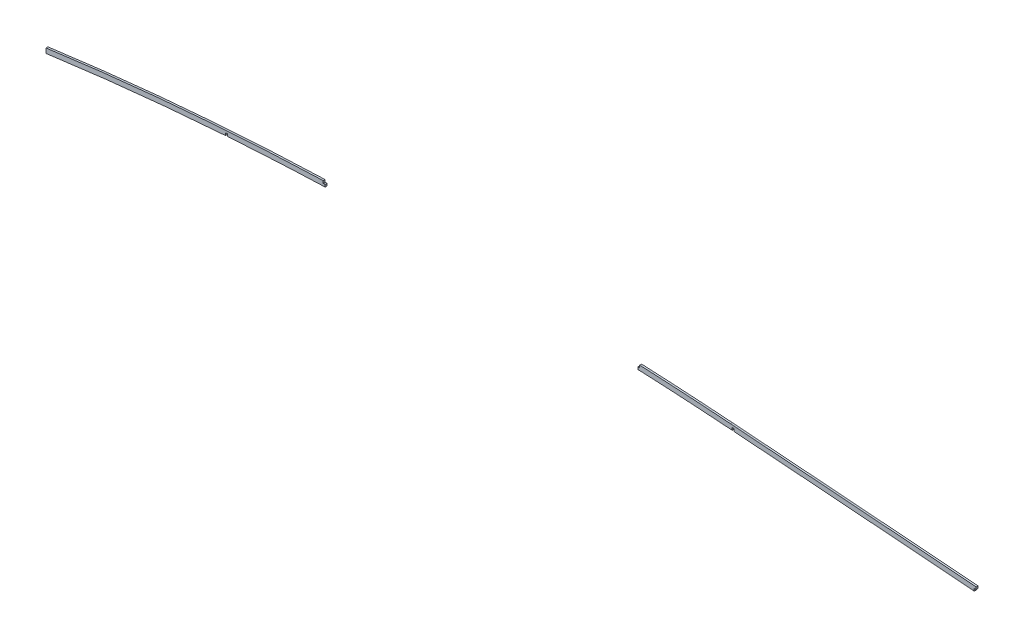
SolidWorks part; units mm, degrees
ref_plane "Front Plane" through (0, 0, 0) normal (0, 0, 1) x (1, 0, 0)
ref_plane "Top Plane" through (0, 0, 0) normal (0, 1, 0) x (1, 0, 0)
ref_plane "Right Plane" through (0, 0, 0) normal (1, 0, 0) x (0, 0, -1)
sketch "Sketch1" plane through (0, 0, 0) normal (0, 0, 1) x (1, 0, 0)
  line L0 (-873.1569, -405.6275) -> (-893.4769, -405.6275) construction
  line L1 (-475.0067, 408.1208) -> (-57.6776, 408.1208)
  line L2 (-475.0067, 382.7208) -> (-57.6776, 382.7208)
  line L3 (-2497.0067, 266.7561) -> (-2493.4723, 241.6032)
  line L4 (2501.9933, 263.2258) -> (2500.0175, 237.9028)
  line L5 (-475.0067, 382.7208) -> (-475.0067, 313.855)
  line L7 (-2493.4723, 241.6032) -> (-2493.4723, 201.2091)
  line L8 (701.2517, 340.7501) -> (691.2517, 340.7501)
  line L10 (691.2517, 340.7501) -> (691.2517, 353.2501)
  line L11 (691.2517, 353.2501) -> (701.2517, 353.2501)
  line L12 (701.2517, 353.2501) -> (701.2517, 365.7751)
  line L13 (2500.0175, 237.9028) -> (2500.0175, 197.7812)
  line L14 (1179.4301, 312.5902) -> (1179.4301, 325.0902) construction
  line L15 (1179.4301, 325.0902) -> (1189.4301, 325.0902) construction
  line L16 (1189.4301, 325.0902) -> (1189.4301, 311.8594) construction
  line L17 (1181.2517, 293.855) -> (1181.2517, 188.8411) construction
  line L18 (-2443.4723, 223.3063) -> (-2443.4723, 248.5402)
  line L19 (2483.0775, 239.2239) -> (2483.0775, 214.1481)
  line L20 (935.6747, 353.6794) -> (935.6747, 9.4968) construction
  line L21 (681.2517, 366.6569) -> (681.2517, 111.1326)
  line L22 (-975.0067, 374.1011) -> (-975.0067, 83.1429)
  line L23 (-975.0067, 349.0863) -> (-965.0067, 349.0863)
  line L24 (-965.0067, 349.0863) -> (-965.0067, 361.5863)
  line L25 (-965.0067, 361.5863) -> (-975.0067, 361.5863)
  line L26 (701.2517, 325.7351) -> (701.2517, 340.7501)
  line L27 (1201.2501, 336.0619) -> (1201.2501, 310.9951)
  line L28 (1191.2501, 324.2264) -> (1201.2501, 324.2264)
  line L29 (1191.2501, 324.2264) -> (1191.2501, 311.7264)
  line L30 (2483.0775, 226.686) -> (2473.0775, 226.686)
  line L31 (2473.0775, 226.686) -> (2473.0775, 214.9276)
  line L32 (-1482.3467, 40.0604) -> (-1482.3467, 248.5402)
  line L33 (-1482.3467, 248.5402) -> (-1482.3467, 322.6417)
  line L34 (-1482.3467, 322.6417) -> (-1482.3467, 335.1417)
  line L35 (-1482.3467, 335.1417) -> (-1492.3467, 335.1417)
  line L36 (-1492.3467, 335.1417) -> (-1492.3467, 321.9409)
  line L38 (-475.0067, 357.7208) -> (-57.6776, 357.7208) construction
  arc A0 (1183.1025, 362.8562) -> (806.4225, 386.1827) centre (-57.6776, -16620.4625) ccw
  arc A1 (806.4225, 386.1827) -> (539.7225, 397.6385) centre (-57.6776, -16620.4625) ccw
  arc A2 (539.7225, 397.6385) -> (-57.6776, 408.1208) centre (-57.6776, -16620.4625) ccw
  arc A3 (-475.0067, 408.1208) -> (-2497.0067, 266.7561) centre (-475.0067, -14123.328) ccw construction
  arc A4 (1183.1025, 362.8562) -> (2501.9933, 263.2258) centre (-18336.3105, -266811.34) cw construction
  arc A5 (1181.2517, 337.5237) -> (2500.0175, 237.9028) centre (-18336.3105, -266811.34) cw
  arc A6 (1181.2517, 337.5237) -> (805.1336, 360.8154) centre (-57.6776, -16620.4625) ccw
  arc A7 (805.1336, 360.8154) -> (538.8314, 372.2542) centre (-57.6776, -16620.4625) ccw
  arc A8 (538.8314, 372.2542) -> (-57.6776, 382.7208) centre (-57.6776, -16620.4625) ccw
  arc A9 (-475.0067, 382.7208) -> (-2493.4723, 241.6032) centre (-475.0067, -14123.328) ccw
  arc A10 (-975.0067, 349.0863) -> (-2443.4723, 223.3063) centre (-475.0067, -14123.328) ccw
  arc A11 (803.865, 335.8476) -> (537.9544, 347.2695) centre (-57.6776, -16620.4625) ccw construction
  arc A12 (803.865, 335.8476) -> (701.2517, 340.7501) centre (-57.6776, -16620.4625) ccw
  arc A13 (1179.4301, 312.5902) -> (803.865, 335.8476) centre (-57.6776, -16620.4625) ccw
  arc A14 (1179.4301, 312.5902) -> (2498.0728, 212.9785) centre (-18336.3105, -266811.34) cw construction
  arc A16 (1179.4301, 312.5902) -> (2483.0775, 214.1481) centre (-18336.3105, -266811.34) cw
  arc A17 (-475.0067, 357.7208) -> (-2489.9937, 216.8464) centre (-475.0067, -14123.328) ccw construction
  arc A20 (537.9544, 347.2695) -> (-57.6776, 357.7208) centre (-57.6776, -16620.4625) ccw construction
  dimension "D1" = 14531.4488
  dimension "D2" = 267886.2793
  dimension "D3" = 17028.5833
  dimension "D4" = 17028.5833
  dimension "D21" = 10
  dimension "D10" = 12.5
  dimension "D27" = 25
  dimension "D5" = 417.3291
  dimension "D6" = 4999
  dimension "D7" = 2022
  dimension "D8" = 1318.8908
  dimension "D9" = 1658.1092
  dimension "D11" = 10
  dimension "D12" = 12.5
  dimension "D14" = 11.82
  dimension "D15" = 25
  dimension "D16" = 50
  dimension "D17" = 16.94
  dimension "D18" = 245.577
  dimension "D19" = 500
  dimension "D20" = 500
  dimension "D13" = 10
  dimension "D22" = 12.5
  dimension "D23" = 20
  dimension "D24" = 10
  dimension "D25" = 12.5
  dimension "D26" = 10
  dimension "D28" = 507.34
  dimension "D29" = 12.5
  dimension "D30" = 10
extrude "Boss-Extrude1" add sketch "Sketch1" along normal blind 10
